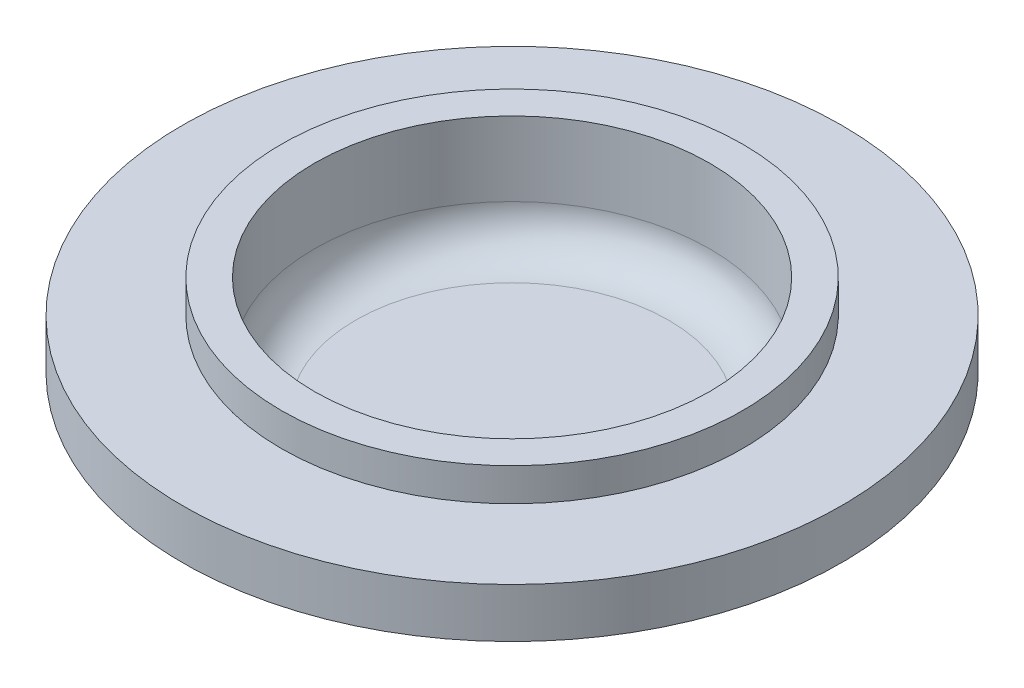
SolidWorks part; units mm, degrees
ref_plane "Alzado" through (0, 0, 0) normal (0, 0, 1) x (1, 0, 0)
ref_plane "Planta" through (0, 0, 0) normal (0, 1, 0) x (1, 0, 0)
ref_plane "Vista lateral" through (0, 0, 0) normal (1, 0, 0) x (0, 0, -1)
sketch "Croquis2" plane through (0, 0, 0) normal (0, 0, 1) x (1, 0, 0)
  line L0 (-28, 14) -> (-28, 18)
  line L1 (0, 0) -> (-28, 0)
  line L2 (0, 0) -> (0, 4)
  line L3 (0, 4) -> (-24, 4)
  line L4 (-28, 0) -> (-28, 8)
  line L5 (-28, 0) -> (-41.3262, 0)
  line L6 (-28, 0) -> (-28, 8)
  line L7 (-28, 18) -> (-24, 18)
  line L9 (-40, 8) -> (-28, 8)
  line L10 (-40, 8) -> (-40, 14)
  line L11 (-40, 14) -> (-28, 14)
  line L13 (-24, 18) -> (-24, 4)
  line L14 (0, 0) -> (0, 50000) construction
  point P13 (-40, 11)
  dimension "D2" = 6
  dimension "D3" = 4
  dimension "D4" = 40
  dimension "D5" = 18
  dimension "D6" = 14
  dimension "D7" = 24
  dimension "D8" = 4
revolve "Revolución2" add sketch "Croquis2" angle 360 about L14
fillet "Redondeo1" radius 5 2 edges at (0, 4, -24) (0, 0, -28)
